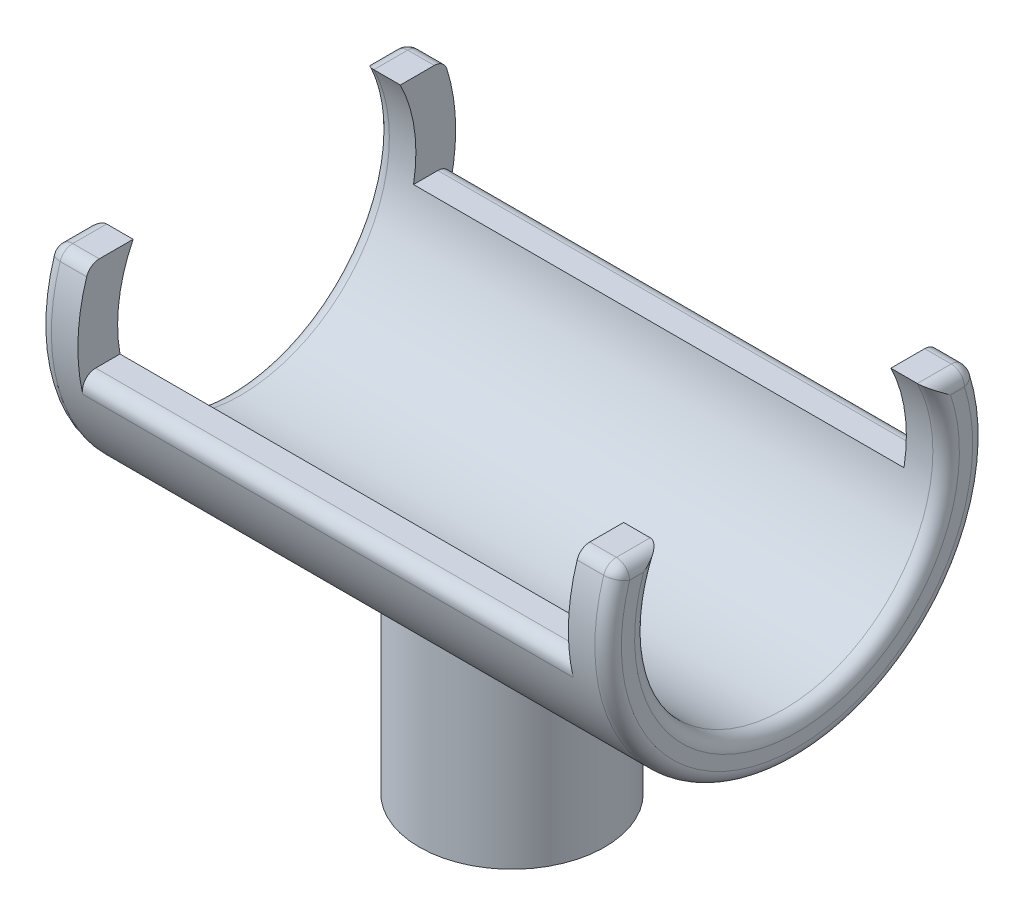
SolidWorks part; units mm, degrees
ref_plane "Front Plane" through (0, 0, 0) normal (0, 0, 1) x (1, 0, 0)
ref_plane "Top Plane" through (0, 0, 0) normal (0, 1, 0) x (1, 0, 0)
ref_plane "Right Plane" through (0, 0, 0) normal (1, 0, 0) x (0, 0, -1)
sketch "Sketch1" plane through (0, 0, 0) normal (0, 1, 0) x (1, 0, 0)
  line L0 (-2.5981, -1.5) -> (2.5981, -1.5)
  arc A0 (2.5981, -1.5) -> (-2.5981, -1.5) centre (0, 0) ccw
  circle A1 centre (0, 0) radius 7
  dimension "D1" = 6
  dimension "D3" = 14
  dimension "D2" = 1.5
extrude "Boss-Extrude1" add sketch "Sketch1" along normal blind 15
sketch "Sketch2" plane through (0, 0, 0) normal (1, 0, 0) x (0, 0, -1)
  line L0 (7, 15) -> (-7, 15) construction
  line L1 (-14.109, 25) -> (-11.0708, 25)
  line L2 (11.0708, 25) -> (14.109, 25)
  arc A0 (-11.0708, 25) -> (11.0708, 25) centre (0, 27) ccw
  arc A1 (-14.109, 25) -> (14.109, 25) centre (0, 27) ccw
  dimension "D1" = 22.5
  dimension "D2" = 28.5
  dimension "D3" = 12
  dimension "D4" = 10
extrude "Boss-Extrude2" add sketch "Sketch2" along normal mid plane 40 separate body
sketch "Sketch3" plane through (20, 0, 0) normal (1, 0, 0) x (0, 0, -1)
  line L0 (-13.344, 32) -> (-10.0778, 32)
  line L1 (10.0778, 32) -> (13.344, 32)
  arc A0 (-10.0778, 32) -> (10.0778, 32) centre (0, 27) ccw
  arc A1 (-13.344, 32) -> (13.344, 32) centre (0, 27) ccw
  dimension "D1" = 22.5
  dimension "D2" = 28.5
  dimension "D3" = 5
extrude "Boss-Extrude3" add sketch "Sketch3" along normal mid plane 3
mirror "Mirror1" about plane through (0, 0, 0) normal (1, 0, 0) of "Boss-Extrude3"
fillet "Fillet1" radius 1 14 edges at (-21.5, 32, 11.7109) (-21.5, 12.75, 0) (-21.5, 32, -11.7109) (-21.5, 15.75, 0) (21.5, 32, -11.7109) (21.5, 12.75, 0) (21.5, 32, 11.7109) (21.5, 15.75, 0) (-20, 32, -13.344) (20, 32, -13.344) (20, 32, 13.344) (-20, 32, 13.344) (0, 25, 14.109) (0, 25, -14.109)
